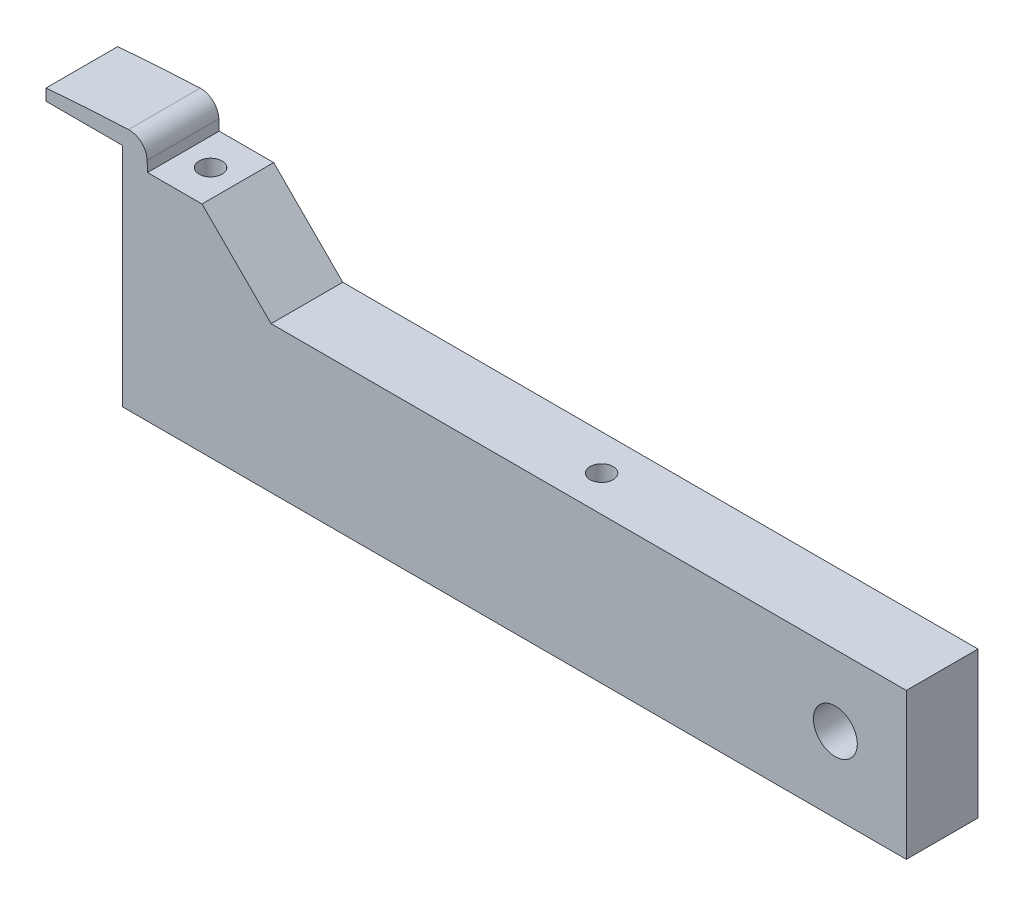
SolidWorks part; units mm, degrees
ref_plane "Front Plane" through (0, 0, 0) normal (0, 0, 1) x (1, 0, 0)
ref_plane "Top Plane" through (0, 0, 0) normal (0, 1, 0) x (1, 0, 0)
ref_plane "Right Plane" through (0, 0, 0) normal (1, 0, 0) x (0, 0, -1)
sketch "Sketch1" plane through (0, 0, 0) normal (0, 0, 1) x (1, 0, 0)
  line L0 (2687.6748, 2686.4465) -> (2687.6748, 2660.5238)
  line L1 (2548.8638, 2700.6286) -> (2535.2748, 2700.6286)
  line L2 (2548.8638, 2700.6286) -> (2548.8638, 2660.5238)
  line L3 (2548.8638, 2660.5238) -> (2687.6748, 2660.5238)
  line L4 (2535.2748, 2700.6286) -> (2535.2748, 2702.6627)
  line L5 (2687.6748, 2686.4465) -> (2575.1488, 2686.4465)
  line L6 (2553.2565, 2698.6868) -> (2553.1966, 2700.5294)
  line L7 (2562.9085, 2698.6868) -> (2575.1488, 2686.4465)
  line L8 (2562.9085, 2698.6868) -> (2553.2565, 2698.6868)
  circle A0 centre (2675.1058, 2673.8775) radius 3.8862
  arc A1 (2553.1966, 2700.5294) -> (2549.888, 2703.5983) centre (2550.0233, 2700.4262) ccw
  spline S0 degree 3 poles (2549.888, 2703.5983) (2545.0096, 2703.3902) (2540.1361, 2703.0886) (2535.2748, 2702.6627) knots 10.936444 10.936444 10.936444 10.936444 11.51433 11.51433 11.51433 11.51433
extrude "Boss-Extrude1" add sketch "Sketch1" along normal blind 12.7
sketch "Sketch2" plane through (0, 2686.4465, 0) normal (0, 1, 0) x (1, 0, 0)
  line L4 (2687.6748, 0) -> (2575.1488, 0)
  line L5 (2575.1488, 0) -> (2575.1488, -12.7)
  line L6 (2575.1488, -12.7) -> (2687.6748, -12.7)
  line L7 (2687.6748, -12.7) -> (2687.6748, 0)
  line L8 (2687.6748, 0) -> (2575.1488, 0)
  line L9 (2575.1488, 0) -> (2575.1488, -12.7)
  line L10 (2575.1488, -12.7) -> (2687.6748, -12.7)
  line L11 (2687.6748, -12.7) -> (2687.6748, 0)
  circle A0 centre (2627.3498, -6.35) radius 2.032
  dimension "D3" = 4.064
  dimension "D2" = 60.325
  dimension "D4" = 6.35
  dimension "D1" = 0
extrude "Cut-Extrude1" cut sketch "Sketch2" against normal through all contours A0
sketch "Sketch3" plane through (0, 2698.6868, 0) normal (0, 1, 0) x (1, 0, 0)
  line L0 (2562.9085, -12.7) -> (2553.2565, -12.7) construction
  line L1 (2562.9085, -12.7) -> (2562.9085, 0) construction
  circle A0 centre (2558.0825, -6.35) radius 2.032
  dimension "D2" = 4.064
  dimension "D1" = 6.35
  dimension "D3" = 4.826
extrude "Cut-Extrude2" cut sketch "Sketch3" against normal through all
